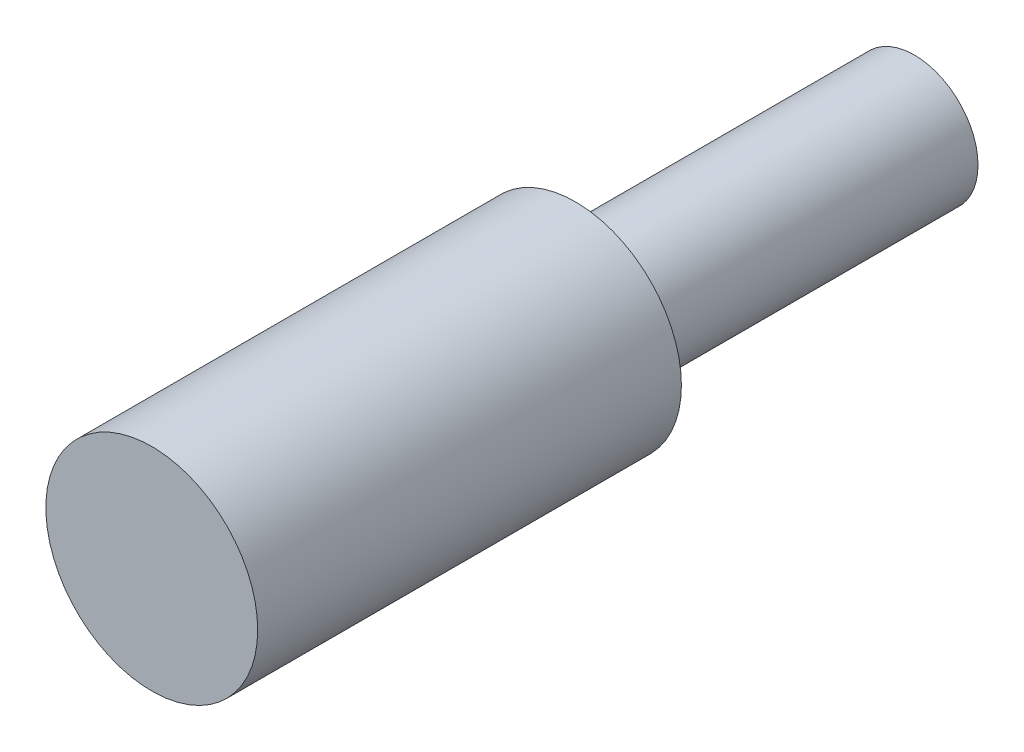
SolidWorks part; units mm, degrees
ref_plane "前视基准面" through (0, 0, 0) normal (0, 0, 1) x (1, 0, 0)
ref_plane "上视基准面" through (0, 0, 0) normal (0, 1, 0) x (1, 0, 0)
ref_plane "右视基准面" through (0, 0, 0) normal (1, 0, 0) x (0, 0, -1)
other "Configuration Table"
sketch "草图1" plane through (0, 0, 0) normal (0, 0, 1) x (1, 0, 0)
  circle A0 centre (0, 0) radius 25
extrude "凸台-拉伸1" add sketch "草图1" along normal blind 100
sketch "草图2" plane through (0, 0, 0) normal (0, 0, 1) x (1, 0, 0)
  circle A0 centre (0, 0) radius 15
extrude "凸台-拉伸2" add sketch "草图2" against normal blind 80
sketch "草图3" plane through (0, 0, 0) normal (0, 1, 0) x (1, 0, 0)
  line L1 (-4, -50) -> (4, -50)
  line L2 (-4, -50) -> (-4, -20)
  line L3 (-4, -20) -> (4, -20)
  line L4 (4, -50) -> (4, -20)
extrude "切除-拉伸1" cut sketch "草图3" along normal blind 4
